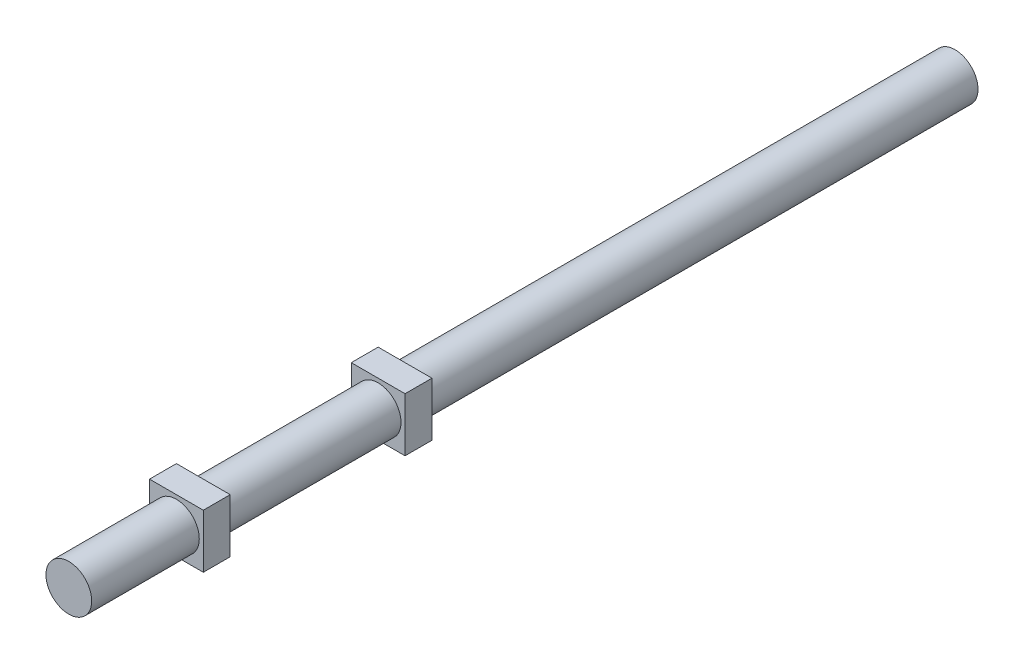
SolidWorks part; units mm, degrees
material "Ductile Iron"
ref_plane "Front Plane" through (0, 0, 0) normal (0, 0, 1) x (1, 0, 0)
ref_plane "Top Plane" through (0, 0, 0) normal (0, 1, 0) x (1, 0, 0)
ref_plane "Right Plane" through (0, 0, 0) normal (1, 0, 0) x (0, 0, -1)
sketch "Sketch1" plane through (0, 0, 0) normal (0, 0, 1) x (1, 0, 0)
  circle A0 centre (0, 0) radius 8.5
  dimension "D1" = 17
extrude "Boss-Extrude1" add sketch "Sketch1" along normal blind 329.5
ref_plane "Plane1" through (0, 0, 279.5) normal (0, 0, 1) x (1, 0, 0)
ref_plane "Plane2" through (0, 0, 204.5) normal (0, 0, 1) x (1, 0, 0)
sketch "Sketch2" plane through (0, 0, 279.5) normal (0, 0, 1) x (1, 0, 0)
  line L1 (-10, 10) -> (10, 10)
  line L2 (-10, 10) -> (-10, -10)
  line L3 (-10, -10) -> (10, -10)
  line L4 (10, 10) -> (10, -10)
  line L5 (-10, 10) -> (10, -10) construction
  line L6 (-10, -10) -> (10, 10) construction
  point P0 (0, 0)
  dimension "D1" = 20
  dimension "D2" = 20
extrude "Boss-Extrude2" add sketch "Sketch2" along normal blind 10
sketch "Sketch3" plane through (0, 0, 204.5) normal (0, 0, 1) x (1, 0, 0)
  line L1 (-10, 10) -> (10, 10)
  line L2 (-10, 10) -> (-10, -10)
  line L3 (-10, -10) -> (10, -10)
  line L4 (10, 10) -> (10, -10)
  line L5 (-10, 10) -> (10, -10) construction
  line L6 (-10, -10) -> (10, 10) construction
  point P0 (0, 0)
extrude "Boss-Extrude3" add sketch "Sketch3" along normal blind 10
